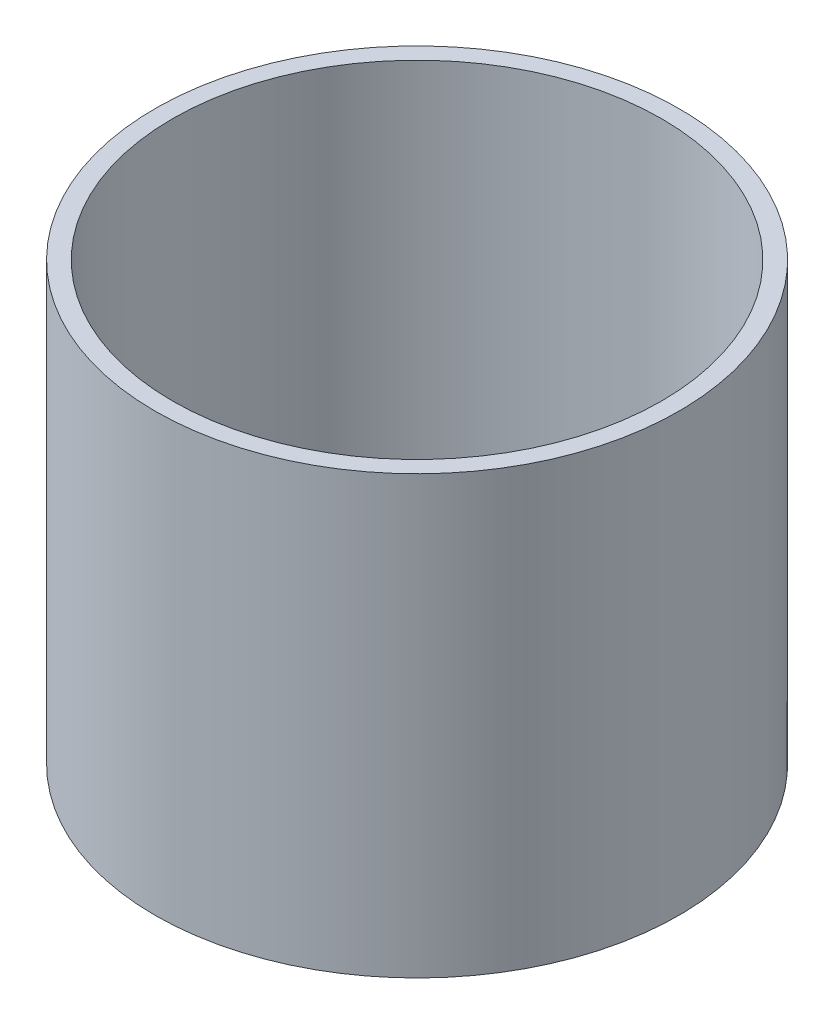
SolidWorks part; units mm, degrees
ref_plane "Front Plane" through (0, 0, 0) normal (0, 0, 1) x (1, 0, 0)
ref_plane "Top Plane" through (0, 0, 0) normal (0, 1, 0) x (1, 0, 0)
ref_plane "Right Plane" through (0, 0, 0) normal (1, 0, 0) x (0, 0, -1)
sketch "Sketch1" plane through (0, 0, 0) normal (0, 1, 0) x (1, 0, 0)
  circle A0 centre (0, 0) radius 28
  circle A1 centre (0, 0) radius 30
  dimension "D1" = 2
  dimension "D2" = 60
extrude "Boss-Extrude1" add sketch "Sketch1" along normal blind 50
